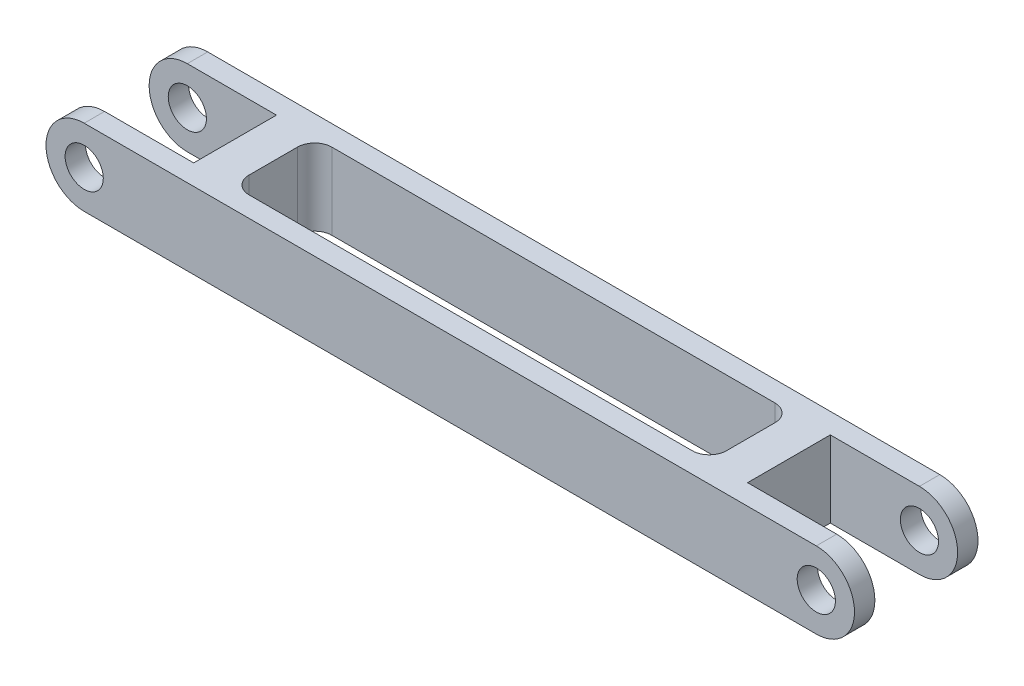
SolidWorks part; units mm, degrees
ref_plane "前视基准面" through (0, 0, 0) normal (0, 0, 1) x (1, 0, 0)
ref_plane "上视基准面" through (0, 0, 0) normal (0, 1, 0) x (1, 0, 0)
ref_plane "右视基准面" through (0, 0, 0) normal (1, 0, 0) x (0, 0, -1)
sketch "草图1" plane through (0, 0, 0) normal (0, 0, 1) x (1, 0, 0)
  line L0 (-57.5, 0) -> (57.5, 0) construction
  line L1 (-57.5, 6) -> (57.5, 6)
  line L2 (-57.5, -6) -> (57.5, -6)
  arc A0 (-57.5, 6) -> (-57.5, -6) centre (-57.5, 0) ccw
  arc A1 (57.5, -6) -> (57.5, 6) centre (57.5, 0) ccw
  circle A2 centre (-57.5, 0) radius 3
  circle A3 centre (57.5, 0) radius 3
  point P3 (0, 0)
  dimension "D3" = 6
  dimension "D4" = 6
  dimension "D1" = 12
  dimension "D2" = 115
extrude "凸台-拉伸1" add sketch "草图1" along normal blind 19.4
sketch "草图2" plane through (0, 6, 0) normal (0, 1, 0) x (1, 0, 0)
  line L0 (-57.5, 0) -> (-63.5, 0) construction
  line L1 (-63.5, -3.2) -> (-43.5, -3.2)
  line L2 (-63.5, -3.2) -> (-63.5, -16.2)
  line L3 (-63.5, -16.2) -> (-43.5, -16.2)
  line L4 (-43.5, -3.2) -> (-43.5, -16.2)
  line L5 (-57.5, -19.4) -> (-57.5, 0) construction
  line L6 (0, 0) -> (0, -26.8414) construction
  line L7 (43.5, -3.2) -> (43.5, -16.2)
  line L8 (63.5, -16.2) -> (43.5, -16.2)
  line L9 (63.5, -3.2) -> (63.5, -16.2)
  line L10 (63.5, -3.2) -> (43.5, -3.2)
  line L11 (57.5, 0) -> (-57.5, 0) construction
  line L12 (-34.8, -3.2) -> (34.8, -3.2)
  line L13 (-37.5, -5.9) -> (-37.5, -13.5)
  line L14 (-34.8, -16.2) -> (34.8, -16.2)
  line L15 (37.5, -5.9) -> (37.5, -13.5)
  line L16 (57.5, -19.4) -> (-57.5, -19.4) construction
  arc A0 (37.5, -13.5) -> (34.8, -16.2) centre (34.8, -13.5) cw
  arc A1 (37.5, -5.9) -> (34.8, -3.2) centre (34.8, -5.9) ccw
  arc A2 (-34.8, -16.2) -> (-37.5, -13.5) centre (-34.8, -13.5) cw
  arc A3 (-34.8, -3.2) -> (-37.5, -5.9) centre (-34.8, -5.9) ccw
  dimension "D9" = 2.7
  dimension "D1" = 13
  dimension "D2" = 3.2
  dimension "D3" = 6
  dimension "D4" = 20
  dimension "D5" = 6
  dimension "D6" = 6
  dimension "D7" = 3.2
  dimension "D8" = 3.2
extrude "切除-拉伸1" cut sketch "草图2" against normal through all
